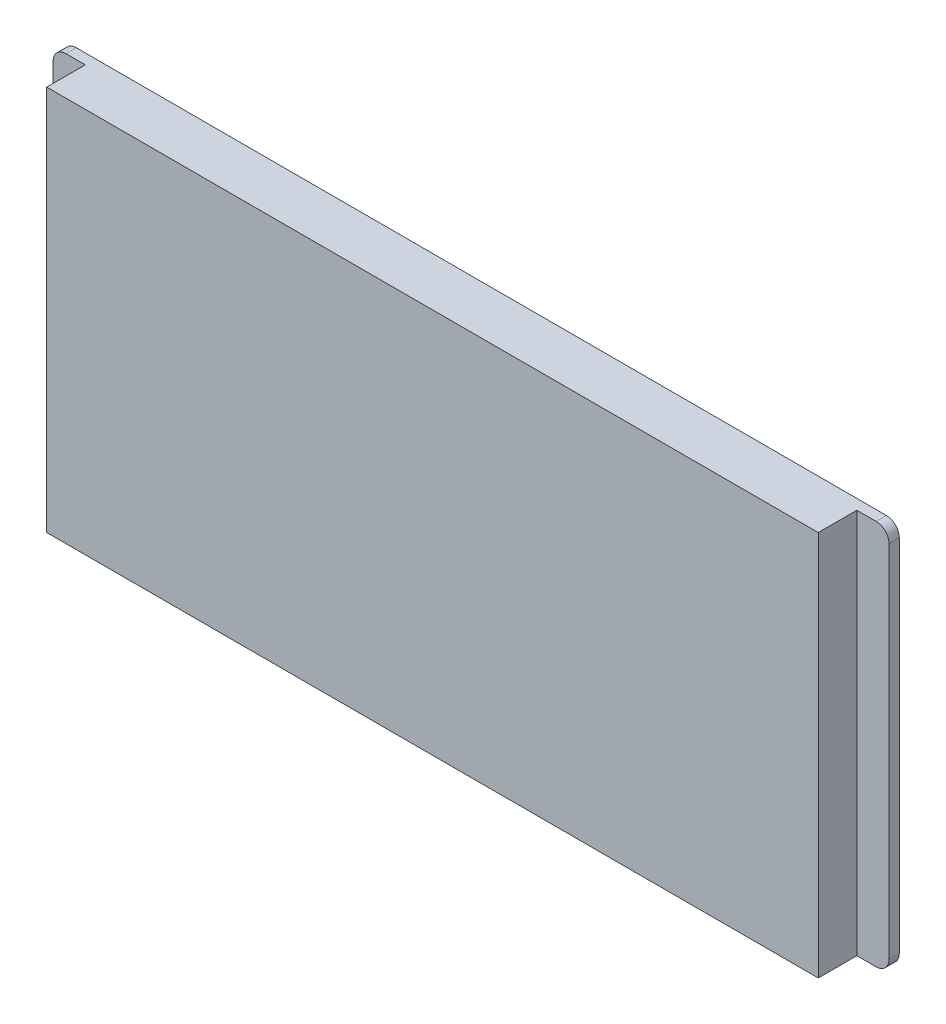
SolidWorks part; units mm, degrees
material "2A12"
ref_plane "前视基准面" through (0, 0, 0) normal (0, 0, 1) x (1, 0, 0)
ref_plane "上视基准面" through (0, 0, 0) normal (0, 1, 0) x (1, 0, 0)
ref_plane "右视基准面" through (0, 0, 0) normal (1, 0, 0) x (0, 0, -1)
sketch "草图1" plane through (0, 0, 0) normal (0, 0, 1) x (1, 0, 0)
  line L1 (60, -30) -> (-60, -30)
  line L2 (60, -30) -> (60, 30)
  line L3 (60, 30) -> (-60, 30)
  line L4 (-60, -30) -> (-60, 30)
  line L5 (60, -30) -> (-60, 30) construction
  line L6 (60, 30) -> (-60, -30) construction
  point P0 (0, 0)
  dimension "D1" = 60
  dimension "D2" = 120
extrude "凸台-拉伸1" add sketch "草图1" along normal blind 7.6
sketch "草图5" plane through (0, 0, 0) normal (0, 0, -1) x (-1, 0, 0)
  line L1 (65, -30) -> (-65, -30)
  line L2 (65, -30) -> (65, 30)
  line L3 (65, 30) -> (-65, 30)
  line L4 (-65, -30) -> (-65, 30)
  line L5 (65, -30) -> (-65, 30) construction
  line L6 (65, 30) -> (-65, -30) construction
  point P0 (0, 0)
  dimension "D1" = 60
  dimension "D2" = 130
extrude "凸台-拉伸2" add sketch "草图5" against normal blind 1.6
fillet "圆角1" radius 2 4 edges at (-65, 30, 0.8) (-65, -30, 0.8) (65, -30, 0.8) (65, 30, 0.8)
